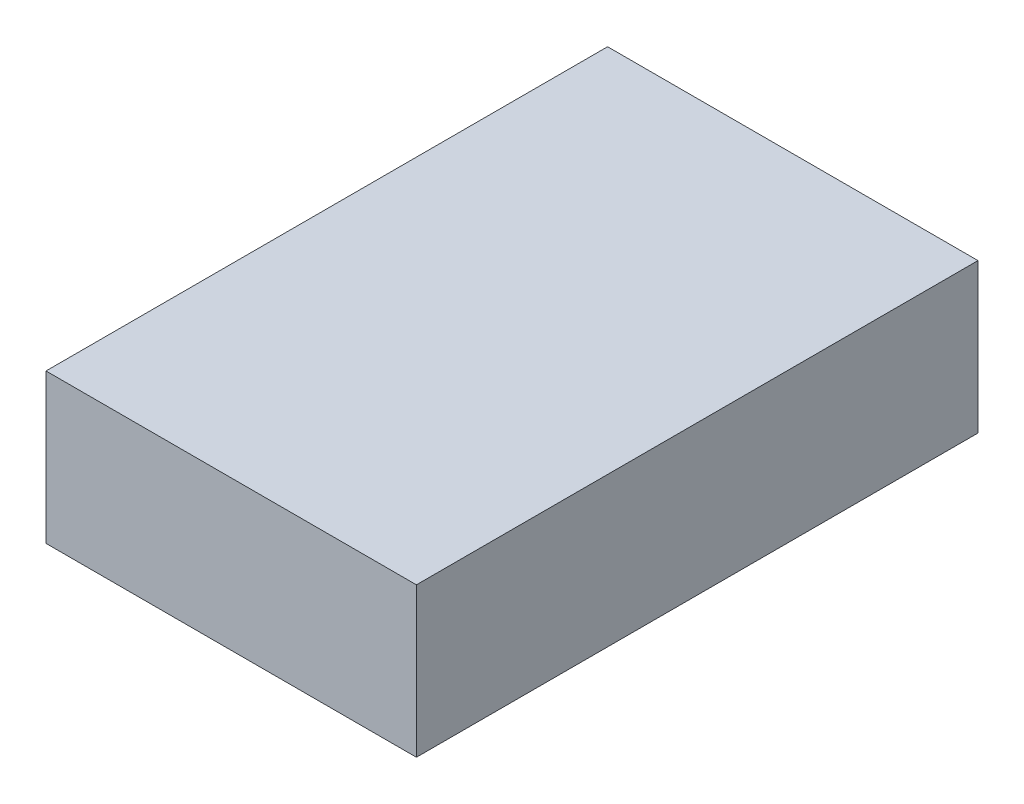
SolidWorks part; units mm, degrees
ref_plane "Front Plane" through (0, 0, 0) normal (0, 0, 1) x (1, 0, 0)
ref_plane "Top Plane" through (0, 0, 0) normal (0, 1, 0) x (1, 0, 0)
ref_plane "Right Plane" through (0, 0, 0) normal (1, 0, 0) x (0, 0, -1)
sketch "Sketch1" plane through (0, 0, 0) normal (0, 1, 0) x (1, 0, 0)
  line L1 (-31, -47) -> (31, -47)
  line L2 (-31, -47) -> (-31, 47)
  line L3 (-31, 47) -> (31, 47)
  line L4 (31, -47) -> (31, 47)
  line L5 (-31, -47) -> (31, 47) construction
  line L6 (-31, 47) -> (31, -47) construction
  point P0 (0, 0)
  dimension "D1" = 94
  dimension "D2" = 62
extrude "Boss-Extrude1" add sketch "Sketch1" along normal blind 25
